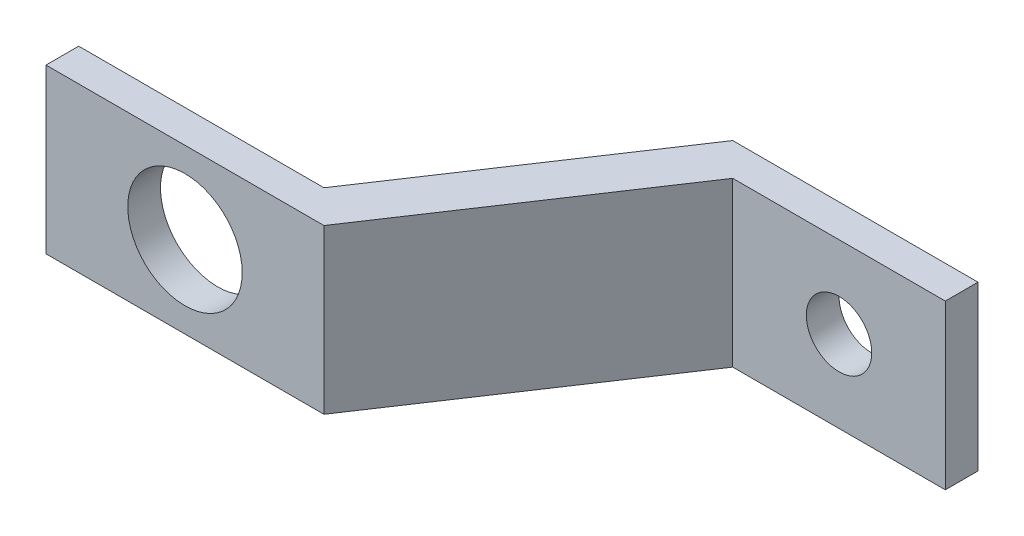
SolidWorks part; units mm, degrees
ref_plane "Front Plane" through (0, 0, 0) normal (0, 0, 1) x (1, 0, 0)
ref_plane "Top Plane" through (0, 0, 0) normal (0, 1, 0) x (1, 0, 0)
ref_plane "Right Plane" through (0, 0, 0) normal (1, 0, 0) x (0, 0, -1)
sketch "Sketch2" plane through (0, 0, 0) normal (0, 1, 0) x (1, 0, 0)
  line L0 (0, 0) -> (15, 0)
  line L1 (15, 0) -> (25, 15)
  line L2 (25, 15) -> (40, 15)
  line L3 (40, 15) -> (40, 13)
  line L4 (40, 13) -> (27, 13)
  line L5 (27, 13) -> (17, -2)
  line L6 (17, -2) -> (0, -2)
  line L7 (0, -2) -> (0, 0)
  point P8 (18.29, 13)
  point P10 (17.1892, 13)
  point P11 (11.6854, -2)
  dimension "D1" = 2
  dimension "D2" = 15
  dimension "D3" = 2
  dimension "D4" = 17
  dimension "D5" = 2
  dimension "D6" = 2
  dimension "D7" = 40
  dimension "D8" = 15
extrude "Boss-Extrude1" add sketch "Sketch2" along normal blind 10
sketch "Sketch3" plane through (0, 0, 2) normal (0, 0, 1) x (1, 0, 0)
  line L0 (8.5, 10) -> (8.5, 0) construction
  line L1 (0, 10) -> (17, 10) construction
  line L2 (0, 0) -> (17, 0) construction
  line L3 (0, 5) -> (17, 5) construction
  line L4 (0, 10) -> (0, 0) construction
  line L5 (17, 10) -> (17, 0) construction
  line L6 (33.5, 10) -> (33.5, 0) construction
  line L7 (27, 10) -> (40, 10) construction
  line L8 (27, 0) -> (40, 0) construction
  circle A0 centre (8.5, 5) radius 3.5
  circle A1 centre (33.5, 5) radius 2
  point P22 (0, 0)
  point P23 (36.7048, 5.4283)
  point P24 (33.5, 6.7809)
  point P25 (33.5, 5)
  dimension "D1" = 7
  dimension "D2" = 4
extrude "Cut-Extrude1" cut sketch "Sketch3" against normal blind 30
